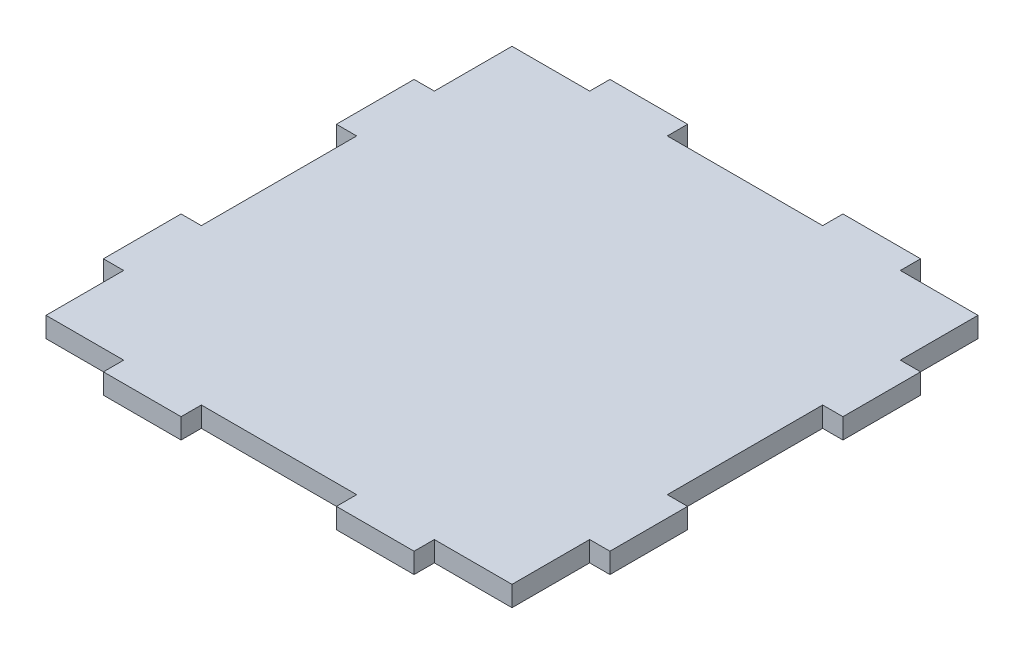
SolidWorks part; units mm, degrees
ref_plane "Front Plane" through (0, 0, 0) normal (0, 0, 1) x (1, 0, 0)
ref_plane "Top Plane" through (0, 0, 0) normal (0, 1, 0) x (1, 0, 0)
ref_plane "Right Plane" through (0, 0, 0) normal (1, 0, 0) x (0, 0, -1)
sketch "Sketch1" plane through (0, 0, 0) normal (0, 1, 0) x (1, 0, 0)
  line L0 (0, 69) -> (-23, 69)
  line L5 (-23, 69) -> (-23, 75)
  line L6 (-23, 75) -> (-46, 75)
  line L7 (-46, 75) -> (-46, 69)
  line L8 (-46, 69) -> (-69, 69)
  line L9 (-69, 69) -> (-69, 46)
  line L10 (-69, 46) -> (-75, 46)
  line L11 (-75, 46) -> (-75, 23)
  line L12 (-75, 23) -> (-69, 23)
  line L13 (-69, 23) -> (-69, 0)
  line L14 (-69, 0) -> (0, 0) construction
  line L15 (0, 69) -> (0, 0) construction
  line L16 (69, 0) -> (69, 23)
  line L17 (69, 23) -> (75, 23)
  line L18 (75, 23) -> (75, 46)
  line L19 (75, 46) -> (69, 46)
  line L20 (69, 46) -> (69, 69)
  line L21 (69, 69) -> (46, 69)
  line L22 (46, 69) -> (46, 75)
  line L23 (46, 75) -> (23, 75)
  line L24 (23, 75) -> (23, 69)
  line L25 (23, 69) -> (0, 69)
  line L26 (0, 69) -> (0, 0) construction
  line L27 (69, 0) -> (0, 0) construction
  line L28 (0, -69) -> (23, -69)
  line L29 (23, -69) -> (23, -75)
  line L30 (23, -75) -> (46, -75)
  line L31 (46, -75) -> (46, -69)
  line L32 (46, -69) -> (69, -69)
  line L33 (69, -69) -> (69, -46)
  line L34 (69, -46) -> (75, -46)
  line L35 (75, -46) -> (75, -23)
  line L36 (75, -23) -> (69, -23)
  line L37 (69, -23) -> (69, 0)
  line L38 (69, 0) -> (0, 0) construction
  line L39 (0, -69) -> (0, 0) construction
  line L40 (-69, 0) -> (-69, -23)
  line L41 (-69, -23) -> (-75, -23)
  line L42 (-75, -23) -> (-75, -46)
  line L43 (-75, -46) -> (-69, -46)
  line L44 (-69, -46) -> (-69, -69)
  line L45 (-69, -69) -> (-46, -69)
  line L46 (-46, -69) -> (-46, -75)
  line L47 (-46, -75) -> (-23, -75)
  line L48 (-23, -75) -> (-23, -69)
  line L49 (-23, -69) -> (0, -69)
  line L50 (0, -69) -> (0, 0) construction
  line L51 (-69, 0) -> (0, 0) construction
  point P5 (-23, 72)
  dimension "D1" = 6
  dimension "D2" = 69
  dimension "D3" = 23
  dimension "D5" = 23
  dimension "D4" = 4
extrude "Boss-Extrude1" add sketch "Sketch1" along normal blind 6
